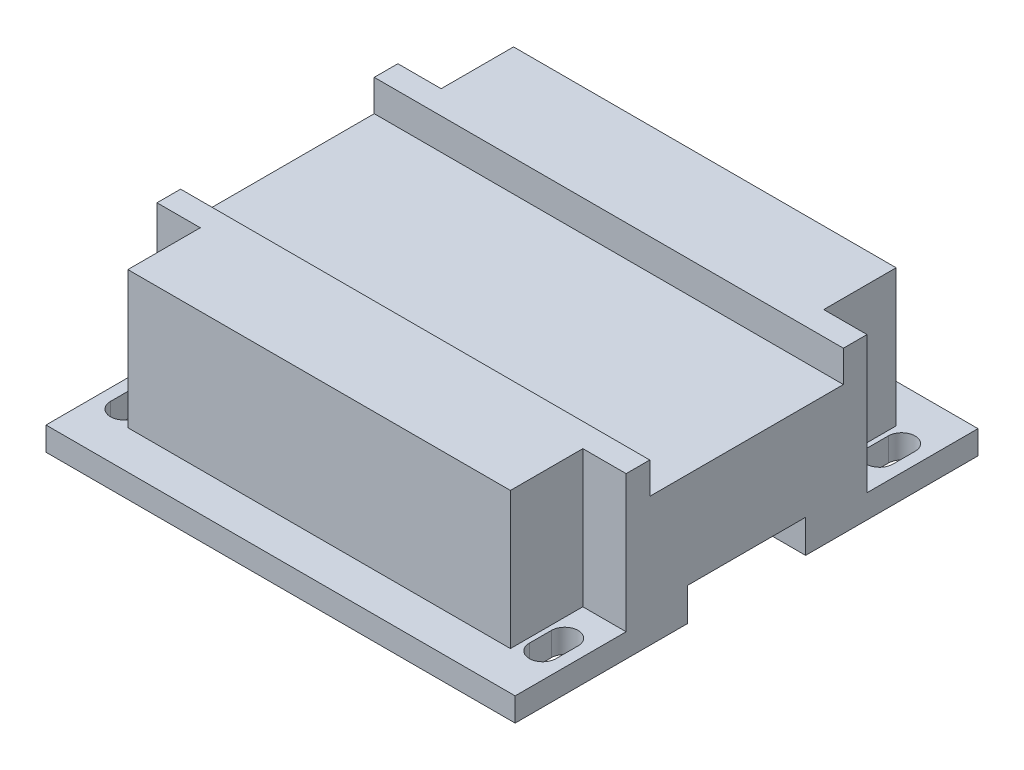
SolidWorks part; units mm, degrees
ref_plane "Front Plane" through (0, 0, 0) normal (0, 0, 1) x (1, 0, 0)
ref_plane "Top Plane" through (0, 0, 0) normal (0, 1, 0) x (1, 0, 0)
ref_plane "Right Plane" through (0, 0, 0) normal (1, 0, 0) x (0, 0, -1)
sketch "Sketch1" plane through (0, 0, 0) normal (0, 1, 0) x (1, 0, 0)
  line L1 (-58.8199, -46.1667) -> (16.8721, -46.1667)
  line L2 (-58.8199, -46.1667) -> (-58.8199, 16.0633)
  line L3 (-58.8199, 16.0633) -> (16.8721, 16.0633)
  line L4 (16.8721, -46.1667) -> (16.8721, 16.0633)
  line L5 (-58.8199, -46.1667) -> (16.8721, 16.0633) construction
  line L6 (-58.8199, 16.0633) -> (16.8721, -46.1667) construction
  point P0 (-20.9739, -15.0517)
  dimension "D1" = 75.692
  dimension "D2" = 62.23
extrude "Boss-Extrude1" add sketch "Sketch1" along normal blind 25.908
sketch "Sketch2" plane through (0, 25.908, 0) normal (0, 1, 0) x (1, 0, 0)
  line L0 (-58.8199, 0.5693) -> (16.8721, 0.5693) construction
  line L1 (-58.8199, 16.0633) -> (-58.8199, -46.1667) construction
  line L2 (16.8721, -46.1667) -> (16.8721, 16.0633) construction
  line L3 (-58.8199, -30.6727) -> (16.8721, -30.6727) construction
  line L4 (-58.8199, -46.1667) -> (16.8721, -46.1667) construction
  line L5 (16.8721, 16.0633) -> (-58.8199, 16.0633) construction
  line L7 (-58.8199, 0.5693) -> (16.8721, 0.5693)
  line L8 (-58.8199, 0.5693) -> (-58.8199, -30.6727)
  line L9 (-58.8199, -30.6727) -> (16.8721, -30.6727)
  line L10 (16.8721, 0.5693) -> (16.8721, -30.6727)
  dimension "D1" = 15.494
  dimension "D2" = 15.494
extrude "Cut-Extrude1" cut sketch "Sketch2" against normal blind 5.08
sketch "Sketch3" plane through (0, 0, 0) normal (0, -1, 0) x (1, 0, 0)
  line L0 (-58.8199, 24.5767) -> (17.0359, 24.5767) construction
  line L1 (-58.8199, -16.0633) -> (-58.8199, 46.1667) construction
  line L2 (-58.8199, 5.5267) -> (16.8721, 5.5267) construction
  line L4 (-58.8199, 46.1667) -> (16.8721, 46.1667) construction
  line L6 (16.8721, 46.1667) -> (16.8721, -16.0633) construction
  line L7 (16.8721, -16.0633) -> (-58.8199, -16.0633) construction
  line L9 (-58.8199, 24.5767) -> (16.8721, 24.5767)
  line L10 (-58.8199, 24.5767) -> (-58.8199, 5.5267)
  line L11 (-58.8199, 5.5267) -> (16.8721, 5.5267)
  line L12 (16.8721, 24.5767) -> (16.8721, 5.5267)
  dimension "D1" = 21.59
  dimension "D2" = 21.59
sketch "Sketch4" plane through (0, 25.908, 0) normal (0, 1, 0) x (1, 0, 0)
  line L0 (16.8721, -34.4827) -> (-58.8199, -34.4827) construction
  line L1 (16.8721, -46.1667) -> (16.8721, -30.6727) construction
  line L2 (-58.8199, -30.6727) -> (-58.8199, -46.1667) construction
  line L3 (16.8721, 4.3793) -> (-58.8199, 4.3793) construction
  line L4 (16.8721, 0.5693) -> (16.8721, 16.0633) construction
  line L5 (-58.8199, 16.0633) -> (-58.8199, 0.5693) construction
  line L6 (-58.8199, -30.6727) -> (16.8721, -30.6727) construction
  line L7 (16.8721, 0.5693) -> (-58.8199, 0.5693) construction
  line L8 (9.8871, -46.1667) -> (9.8871, 16.0633) construction
  line L9 (-58.8199, -46.1667) -> (16.8721, -46.1667) construction
  line L10 (16.8721, 16.0633) -> (-58.8199, 16.0633) construction
  line L11 (-51.8349, -46.1667) -> (-51.8349, 16.0633) construction
  line L13 (9.8871, -34.4827) -> (16.8721, -34.4827)
  line L14 (9.8871, -34.4827) -> (9.8871, -46.1667)
  line L15 (9.8871, -46.1667) -> (16.8721, -46.1667)
  line L16 (16.8721, -34.4827) -> (16.8721, -46.1667)
  line L17 (-51.8349, -34.4827) -> (-58.8199, -34.4827)
  line L18 (-51.8349, -34.4827) -> (-51.8349, -46.1667)
  line L19 (-51.8349, -46.1667) -> (-58.8199, -46.1667)
  line L20 (-58.8199, -34.4827) -> (-58.8199, -46.1667)
  line L21 (-51.8349, 4.3793) -> (-58.8199, 4.3793)
  line L22 (-51.8349, 4.3793) -> (-51.8349, 16.0633)
  line L23 (-51.8349, 16.0633) -> (-58.8199, 16.0633)
  line L24 (-58.8199, 4.3793) -> (-58.8199, 16.0633)
  line L25 (9.8871, 4.3793) -> (16.8721, 4.3793)
  line L26 (9.8871, 4.3793) -> (9.8871, 16.0633)
  line L27 (9.8871, 16.0633) -> (16.8721, 16.0633)
  line L28 (16.8721, 4.3793) -> (16.8721, 16.0633)
  dimension "D1" = 3.81
  dimension "D2" = 3.81
  dimension "D3" = 6.985
  dimension "D4" = 6.985
extrude "Cut-Extrude4" cut sketch "Sketch4" against normal blind 22.098
extrude "Cut-Extrude5" cut sketch "Sketch3" against normal blind 5.334
sketch "Sketch8" plane through (0, 0, 46.1667) normal (0, 0, 1) x (1, 0, 0)
  line L0 (-58.8199, 0) -> (16.8721, 0) construction
  line L1 (-58.8199, 3.81) -> (16.8721, 3.81)
  line L2 (-58.8199, 3.81) -> (-58.8199, 0)
  line L3 (-58.8199, 0) -> (16.8721, 0)
  line L4 (16.8721, 3.81) -> (16.8721, 0)
extrude "Boss-Extrude2" add sketch "Sketch8" along normal blind 6.223
sketch "Sketch9" plane through (0, 0, -16.0633) normal (0, 0, -1) x (-1, 0, 0)
  line L0 (-16.8721, 3.81) -> (-16.8721, 0) construction
  line L1 (-16.8721, 3.81) -> (58.8199, 3.81)
  line L2 (-16.8721, 3.81) -> (-16.8721, 0)
  line L3 (-16.8721, 0) -> (58.8199, 0)
  line L4 (58.8199, 3.81) -> (58.8199, 0)
  line L5 (-16.8721, 3.81) -> (-9.8871, 3.81) construction
extrude "Boss-Extrude3" add sketch "Sketch9" along normal blind 6.223
sketch "Sketch7" plane through (0, 0, 0) normal (0, -1, 0) x (1, 0, 0)
  line L0 (-58.3863, 43.8807) -> (16.8721, 43.8807) construction
  line L1 (16.8721, 52.3897) -> (16.8721, 24.5767) construction
  line L2 (-54.7559, 46.1667) -> (-54.7559, 43.8807) construction
  line L3 (-58.8199, 46.1667) -> (16.8721, 46.1667) construction
  line L4 (16.8721, -16.0633) -> (-58.8199, -16.0633) construction
  line L5 (-54.7559, 40.3247) -> (16.8721, 40.3247) construction
  line L6 (-58.8199, 24.5767) -> (-58.8199, 52.3897) construction
  line L7 (12.8081, 46.1667) -> (12.8081, 43.8807) construction
  line L8 (16.8721, -22.2863) -> (-58.8199, -22.2863) construction
  line L9 (-54.7559, -14.0313) -> (-54.7559, -16.0633) construction
  line L10 (-58.8199, -14.0313) -> (16.8721, -14.0313) construction
  line L11 (-58.8199, -22.2863) -> (-58.8199, 5.5267) construction
  line L12 (16.8721, 5.5267) -> (16.8721, -22.2863) construction
  line L13 (-58.8199, -10.4753) -> (16.8721, -10.4753) construction
  line L14 (-58.8199, 52.3897) -> (16.8721, 52.3897) construction
  line L16 (12.8081, -14.0313) -> (12.8081, -16.0633) construction
  line L17 (12.8081, 40.3247) -> (12.8081, -10.4753) construction
  line L18 (-56.9149, 43.8807) -> (-56.9149, 40.3247)
  line L19 (10.6491, 43.8807) -> (10.6491, 40.3247)
  line L20 (-52.5969, 43.8807) -> (-52.5969, 40.3247)
  line L21 (14.9671, 43.8807) -> (14.9671, 40.3247)
  line L22 (-54.7559, 40.3247) -> (-54.7559, -10.4753) construction
  line L24 (10.6491, -10.4753) -> (10.6491, -14.0313)
  line L25 (-56.9149, -10.4753) -> (-56.9149, -14.0313)
  line L26 (14.9671, -10.4753) -> (14.9671, -14.0313)
  line L27 (-52.5969, -10.4753) -> (-52.5969, -14.0313)
  arc A0 (-56.9149, 43.8807) -> (-52.5969, 43.8807) centre (-54.7559, 43.8807) cw
  arc A1 (-56.9149, 40.3247) -> (-52.5969, 40.3247) centre (-54.7559, 40.3247) ccw
  arc A2 (10.6491, 43.8807) -> (14.9671, 43.8807) centre (12.8081, 43.8807) cw
  arc A3 (10.6491, 40.3247) -> (14.9671, 40.3247) centre (12.8081, 40.3247) ccw
  arc A4 (10.6491, -10.4753) -> (14.9671, -10.4753) centre (12.8081, -10.4753) cw
  arc A5 (10.6491, -14.0313) -> (14.9671, -14.0313) centre (12.8081, -14.0313) ccw
  arc A6 (-56.9149, -10.4753) -> (-52.5969, -10.4753) centre (-54.7559, -10.4753) cw
  arc A7 (-56.9149, -14.0313) -> (-52.5969, -14.0313) centre (-54.7559, -14.0313) ccw
  dimension "D1" = 8.509
  dimension "D2" = 3.556
  dimension "D3" = 4.064
  dimension "D4" = 4.064
  dimension "D5" = 8.255
  dimension "D6" = 3.556
extrude "Cut-Extrude6" cut sketch "Sketch7" against normal up to next
